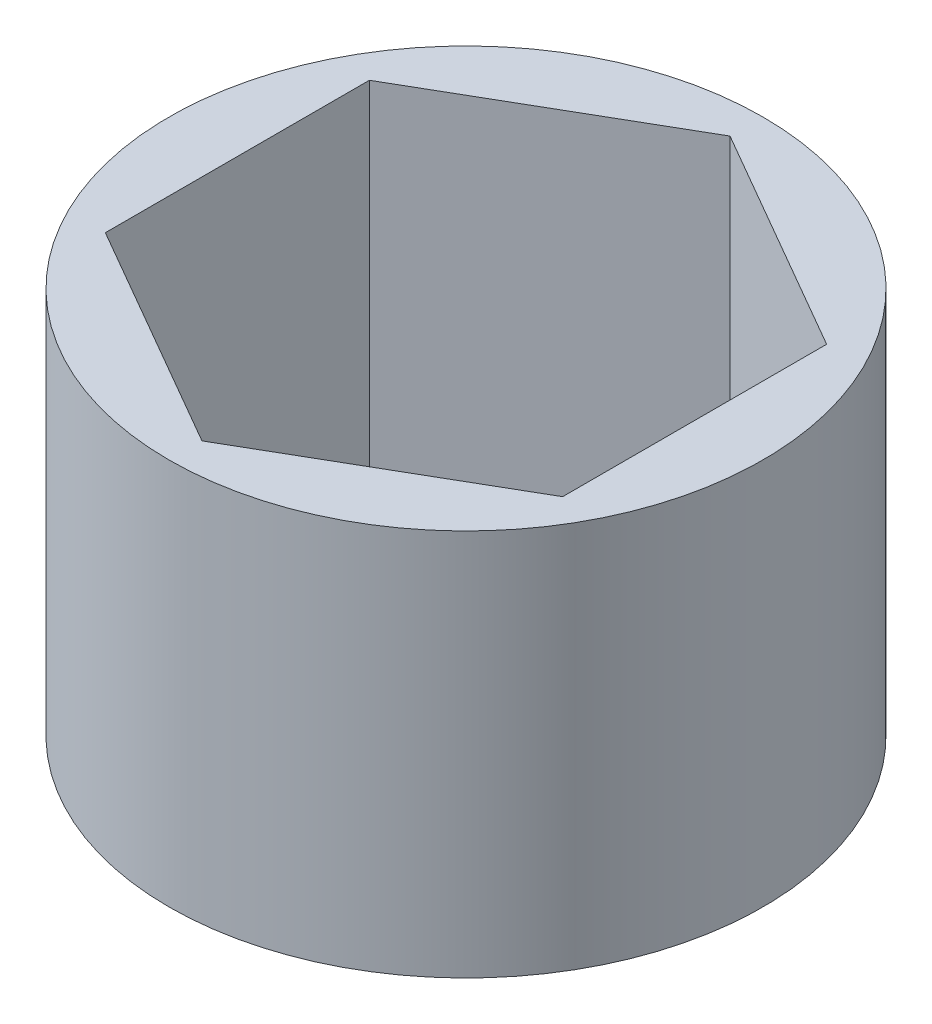
SolidWorks part; units mm, degrees
ref_plane "Front Plane" through (0, 0, 0) normal (0, 0, 1) x (1, 0, 0)
ref_plane "Top Plane" through (0, 0, 0) normal (0, 1, 0) x (1, 0, 0)
ref_plane "Right Plane" through (0, 0, 0) normal (1, 0, 0) x (0, 0, -1)
sketch "Sketch1" plane through (0, 0, 0) normal (0, 1, 0) x (1, 0, 0)
  line L1 (0, 7.7942) -> (-6.75, 3.8971)
  line L2 (-6.75, 3.8971) -> (-6.75, -3.8971)
  line L3 (-6.75, -3.8971) -> (0, -7.7942)
  line L4 (0, -7.7942) -> (6.75, -3.8971)
  line L5 (6.75, -3.8971) -> (6.75, 3.8971)
  line L6 (6.75, 3.8971) -> (0, 7.7942)
  circle A0 centre (0, 0) radius 8.7688
  circle A1 centre (0, 0) radius 6.75 construction
  dimension "D1" = 13.5
extrude "Boss-Extrude1" add sketch "Sketch1" along normal blind 11.43
